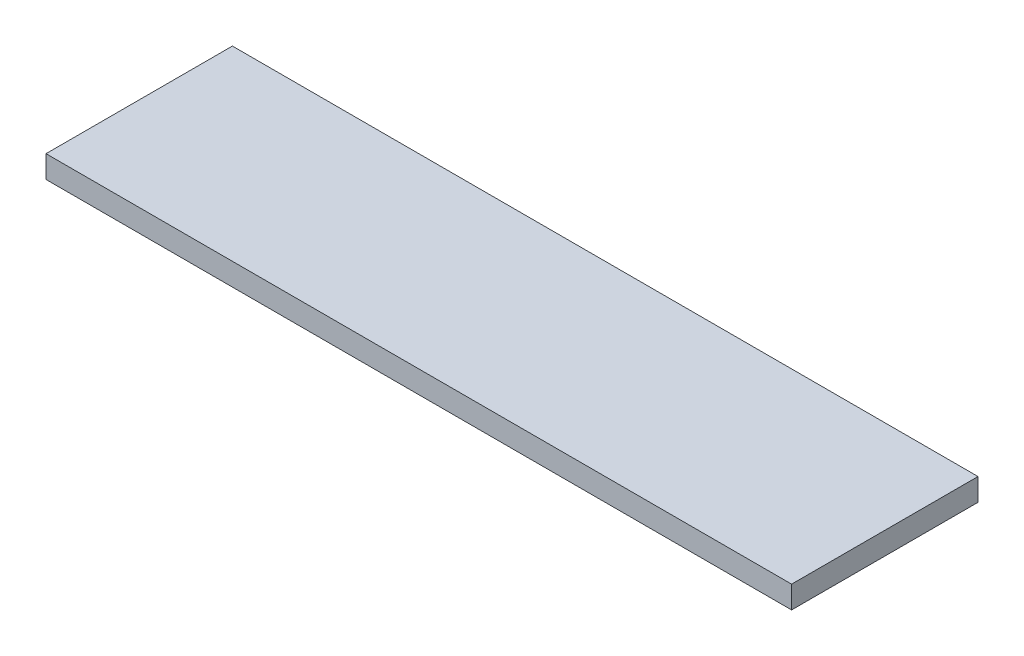
SolidWorks part; units mm, degrees
material "AISI 304"
ref_plane "正面" through (0, 0, 0) normal (0, 0, 1) x (1, 0, 0)
ref_plane "平面" through (0, 0, 0) normal (0, 1, 0) x (1, 0, 0)
ref_plane "右側面" through (0, 0, 0) normal (1, 0, 0) x (0, 0, -1)
sketch "ｽｹｯﾁ1" plane through (0, 0, 0) normal (0, 1, 0) x (1, 0, 0)
  line L0 (-100, 25) -> (100, 25)
  line L1 (100, 25) -> (100, -25)
  line L2 (100, -25) -> (-100, -25)
  line L3 (-100, -25) -> (-100, 25)
  line L4 (0, 0) -> (0, -25) construction
  line L5 (0, 0) -> (25, 0) construction
  dimension "D1" = 200
  dimension "D2" = 50
extrude "フラットバー 切断" add sketch "ｽｹｯﾁ1" along normal mid plane 6
equation "\"BALLAST_L\" = 200"
equation "\"D1@ｽｹｯﾁ1\" = \"BALLAST_L\""
equation "\"BALLAST_W\" = 50"
equation "\"D2@ｽｹｯﾁ1\" = \"BALLAST_W\""
equation "\"BALLAST_T\" = 6"
equation "\"D1@フラットバー 切断\" = \"BALLAST_T\""
